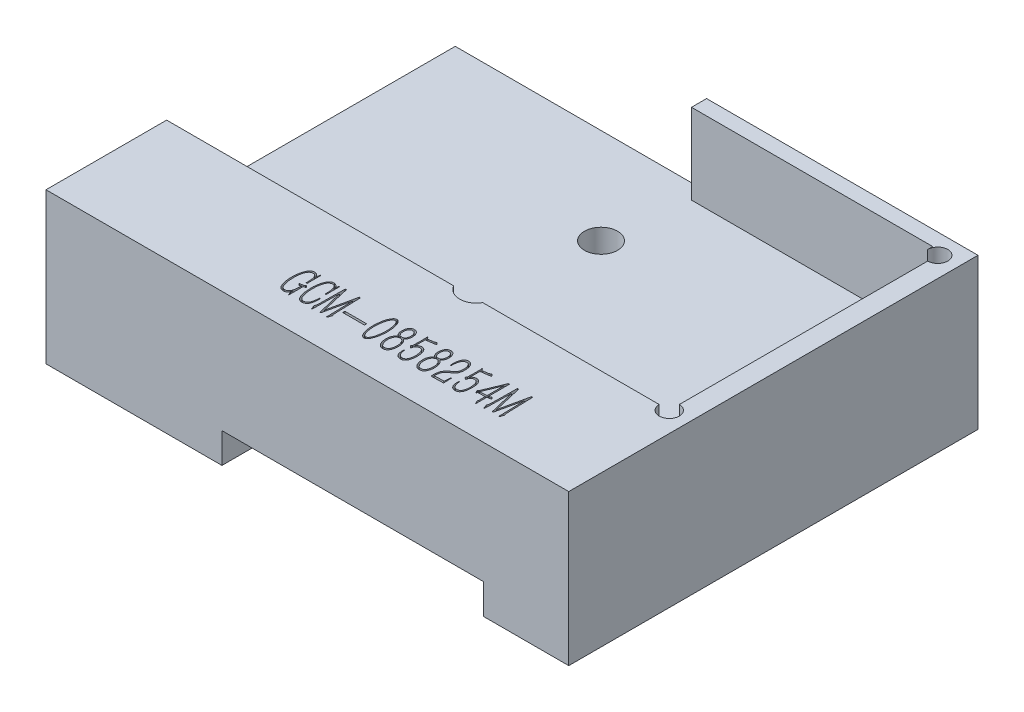
SolidWorks part; units mm, degrees
material "6061 合金"
ref_plane "前视基准面" through (0, 0, 0) normal (0, 0, 1) x (1, 0, 0)
ref_plane "上视基准面" through (0, 0, 0) normal (0, 1, 0) x (1, 0, 0)
ref_plane "右视基准面" through (0, 0, 0) normal (1, 0, 0) x (0, 0, -1)
sketch "草图1" plane through (0, 0, 0) normal (0, 1, 0) x (1, 0, 0)
  line L1 (-25, 13.355) -> (25, 13.355)
  line L2 (-25, 13.355) -> (-25, -13.355)
  line L3 (-25, -13.355) -> (25, -13.355)
  line L4 (25, 13.355) -> (25, -13.355)
  line L5 (-25, 13.355) -> (25, -13.355) construction
  line L6 (-25, -13.355) -> (25, 13.355) construction
  point P0 (0, 0)
  dimension "D1" = 50
  dimension "D2" = 26.71
extrude "凸台-拉伸1" add sketch "草图1" along normal blind 6
sketch "草图2" plane through (0, 6, 0) normal (0, 1, 0) x (1, 0, 0)
  line L1 (25, 13.355) -> (-25, 13.355) construction
  line L3 (25, 13.355) -> (-25, 13.355)
  line L12 (-25, -13.355) -> (25, -13.355) construction
  line L13 (-25, -13.355) -> (25, -13.355)
  line L19 (25, -13.355) -> (25, 13.355) construction
  line L20 (25, -13.355) -> (25, 13.355)
  line L21 (-25, -15.355) -> (27, -15.355)
  line L22 (27, -15.355) -> (27, 15.355)
  line L23 (27, 15.355) -> (-25, 15.355)
  line L24 (-25, -15.355) -> (-25, -13.355)
  line L25 (-25, 13.355) -> (-25, 15.355)
  dimension "D1" = 2
extrude "凸台-拉伸2" add sketch "草图2" along normal blind 8 and the other way through all
sketch "草图3" plane through (0, 6, 0) normal (0, 1, 0) x (1, 0, 0)
  line L0 (-1, 13.355) -> (-1, 5.855) construction
  line L1 (25, -13.355) -> (25, 13.355) construction
  line L3 (25, 13.355) -> (-25, 13.355) construction
  line L5 (-1, 5.855) -> (25, 5.855) construction
  circle A0 centre (-1, 5.855) radius 1.3881
  dimension "D1" = 7.5
  dimension "D2" = 26
hole_wizard "M4 螺纹孔1" [suppressed] positions "3D草图1" profile "草图4" tap size "M4" standard "GB"
sketch3d "3D草图1"
  point P0 (-1, 6, -5.855)
sketch "草图4" plane through (-1, 6, -5.855) normal (1, 0, 0) x (0, 0, 1)
  line L0 (0, 0) -> (0, 11.0914)
  line L1 (0, 11.0914) -> (1.65, 10.1)
  line L2 (1.65, 10.1) -> (1.65, 0)
  line L5 (1.65, 0) -> (0, 0)
  line L10 (0, 11.0914) -> (-1.65, 10.1) construction
  line L11 (0, -6.35) -> (0, 107.95) construction
  dimension "螺纹孔钻头直径" = 3.3
  dimension "螺纹孔钻头深度" = 10.1
  dimension "导头角度" = 118
cosmetic thread "孔螺蚊线1" [suppressed] parameters "D1"=2.4, "D2"=4
sketch "草图12" plane through (-25, 0, 0) normal (-1, 0, 0) x (0, 0, 1)
  line L1 (-13.355, 6) -> (-15.355, 6)
  line L2 (-13.355, 6) -> (-13.355, 14)
  line L3 (-13.355, 14) -> (-15.355, 14)
  line L4 (-15.355, 6) -> (-15.355, 14)
extrude "切除-拉伸5" cut sketch "草图12" against normal blind 25
sketch "草图13" plane through (0, 14, 0) normal (0, 1, 0) x (1, 0, 0)
  circle A0 centre (25, -13.355) radius 1
  circle A1 centre (25, 13.355) radius 1
extrude "切除-拉伸6" cut sketch "草图13" against normal up to surface (8 mm away) up to face at (0, 6, -5.1183)
sketch "草图15" plane through (0, 0, 15.355) normal (0, 0, 1) x (1, 0, 0)
  line L4 (27, 0) -> (27, 14)
  line L5 (27, 14) -> (-25, 14)
  line L6 (-25, 14) -> (-25, 0)
  line L7 (-25, 0) -> (27, 0)
  line L8 (27, 0) -> (27, 14)
  line L9 (27, 14) -> (-25, 14)
  line L10 (-25, 14) -> (-25, 0)
  line L11 (-25, 0) -> (27, 0)
  dimension "D1" = 0
extrude "凸台-拉伸3" add sketch "草图15" along normal blind 10
sketch "草图5" plane through (0, 0, 0) normal (0, -1, 0) x (1, 0, 0)
  line L0 (-7.4968, 0.0619) -> (-7.4968, 25.0555) construction
  line L1 (-7.4968, 25.0555) -> (17.5032, 25.0555)
  line L2 (-7.4968, 25.0555) -> (-7.4968, 0.0555)
  line L3 (-7.4968, 0.0555) -> (17.5032, 0.0555)
  line L4 (17.5032, 25.0555) -> (17.5032, 0.0555)
  line L5 (-7.4968, 25.0555) -> (17.5032, 0.0555) construction
  line L6 (-7.4968, 0.0555) -> (17.5032, 25.0555) construction
  line L7 (-7.4968, 25.0555) -> (17.4968, 25.0555) construction
  circle A0 centre (5.0032, 12.5555) radius 1.1939
  dimension "D1" = 25
  dimension "D2" = 25
extrude "切除-拉伸1" cut sketch "草图5" against normal blind 2
sketch "草图6" plane through (0, 2, 0) normal (0, -1, 0) x (1, 0, 0)
  line L0 (5.0032, 25.0555) -> (5.0032, 0.0555) construction
  line L3 (5.0032, 12.5555) -> (-7.4968, 12.5555) construction
  line L6 (-7.4968, 25.0555) -> (-7.4968, 0.0555) construction
  line L8 (17.5032, 25.0555) -> (-7.4968, 25.0555) construction
  dimension "D1" = 25
  dimension "D2" = 12.5
hole_wizard "M4 螺纹孔2" positions "3D草图2" profile "草图7" tap size "M4" standard "GB" end condition through all
sketch3d "3D草图2"
  point P0 (5.0032, 2, 12.5555)
cosmetic thread "孔螺蚊线2" parameters "D2"=4
sketch "草图7" plane through (5.0032, 2, 12.5555) normal (1, 0, 0) x (0, 0, -1)
  line L0 (0, 0) -> (0, 12)
  line L1 (0, 12) -> (1.65, 12)
  line L2 (1.65, 12) -> (1.65, 0)
  line L5 (1.65, 0) -> (0, 0)
  line L11 (0, -6.35) -> (0, 107.95) construction
  dimension "通孔螺纹孔钻头直径" = 3.3
  dimension "通孔螺纹孔钻头深度" = 12
sketch "草图16" plane through (0, 0, 25.0555) normal (0, 0, -1) x (-1, 0, 0)
  line L4 (-17.5032, 0) -> (7.4968, 0)
  line L5 (7.4968, 0) -> (7.4968, 2)
  line L6 (7.4968, 2) -> (-17.5032, 2)
  line L7 (-17.5032, 2) -> (-17.5032, 0)
  line L8 (-17.5032, 0) -> (7.4968, 0)
  line L9 (7.4968, 0) -> (7.4968, 2)
  line L10 (7.4968, 2) -> (-17.5032, 2)
  line L11 (-17.5032, 2) -> (-17.5032, 0)
  dimension "D1" = 0
extrude "切除-拉伸7" cut sketch "草图16" against normal through all
sketch "草图17" plane through (17.5032, 0, 0) normal (-1, 0, 0) x (0, 0, 1)
  line L4 (0.0555, 0) -> (25.355, 0)
  line L5 (25.355, 0) -> (25.355, 2)
  line L6 (25.355, 2) -> (0.0555, 2)
  line L7 (0.0555, 2) -> (0.0555, 0)
  line L8 (0.0555, 0) -> (25.355, 0)
  line L9 (25.355, 0) -> (25.355, 2)
  line L10 (25.355, 2) -> (0.0555, 2)
  line L11 (0.0555, 2) -> (0.0555, 0)
  dimension "D1" = 0
extrude "切除-拉伸8" cut sketch "草图17" against normal blind 1
sketch "草图18" plane through (0, 0, 0) normal (0, -1, 0) x (-1, 0, 0)
  circle A0 centre (7.4968, -0.0555) radius 1
extrude "切除-拉伸9" cut sketch "草图18" against normal up to surface (2 mm away) up to face at (5.0032, 2, 10.9055)
fillet "圆角1" radius 1 1 edges at (18.5032, 1, 0.0555)
sketch "草图19" plane through (0, 0, -13.355) normal (0, 0, 1) x (1, 0, 0)
  line L4 (24, 14) -> (0, 14)
  line L5 (0, 14) -> (0, 6)
  line L6 (0, 6) -> (24, 6)
  line L7 (24, 6) -> (24, 14)
  line L8 (24, 14) -> (0, 14)
  line L9 (0, 14) -> (0, 6)
  line L10 (0, 6) -> (24, 6)
  line L12 (24, 6) -> (24, 14)
  dimension "D1" = 0
extrude "切除-拉伸10" cut sketch "草图19" against normal blind 0.5
sketch "草图20" plane through (0, 14, 0) normal (0, 1, 0) x (1, 0, 0)
  text T0 "GCM-0858254M "
extrude "切除-拉伸11" cut sketch "草图20" against normal blind 0.5
sketch "草图21" plane through (0, 0, 0) normal (0, -1, 0) x (1, 0, 0)
  line L8 (17.5032, 0.0555) -> (-6.4968, 0.0555)
  line L9 (-7.4968, 1.0555) -> (-7.4968, 25.355)
  line L10 (-7.4968, 25.355) -> (-25, 25.355)
  line L11 (-25, 25.355) -> (-25, -15.355)
  line L12 (-25, -15.355) -> (27, -15.355)
  line L13 (27, -15.355) -> (27, 25.355)
  line L14 (27, 25.355) -> (18.5032, 25.355)
  line L15 (18.5032, 25.355) -> (18.5032, 1.0555)
  line L16 (17.5032, 0.0555) -> (-6.4968, 0.0555)
  line L17 (-7.4968, 1.0555) -> (-7.4968, 25.355)
  line L18 (-7.4968, 25.355) -> (-25, 25.355)
  line L19 (-25, 25.355) -> (-25, -15.355)
  line L20 (-25, -15.355) -> (27, -15.355)
  line L21 (27, -15.355) -> (27, 25.355)
  line L22 (27, 25.355) -> (18.5032, 25.355)
  line L23 (18.5032, 25.355) -> (18.5032, 1.0555)
  arc A2 (-7.4968, 1.0555) -> (-6.4968, 0.0555) centre (-7.4968, 0.0555) ccw
  arc A3 (17.5032, 0.0555) -> (18.5032, 1.0555) centre (17.5032, 1.0555) ccw
  arc A4 (-7.4968, 1.0555) -> (-6.4968, 0.0555) centre (-7.4968, 0.0555) ccw
  arc A5 (17.5032, 0.0555) -> (18.5032, 1.0555) centre (17.5032, 1.0555) ccw
  dimension "D1" = 0
extrude "凸台-拉伸4" add sketch "草图21" along normal blind 1
hole_wizard "M4 螺纹孔3" positions "3D草图3" profile "草图22" tap size "M4" standard "GB" end condition through all
sketch3d "3D草图3"
  point P0 (-1, 6, -5.855)
sketch "草图22" plane through (-1, 6, -5.855) normal (1, 0, 0) x (0, 0, 1)
  line L0 (0, 0) -> (0, 7)
  line L1 (0, 7) -> (1.65, 7)
  line L2 (1.65, 7) -> (1.65, 0)
  line L5 (1.65, 0) -> (0, 0)
  line L11 (0, -6.35) -> (0, 107.95) construction
  dimension "通孔螺纹孔钻头直径" = 3.3
  dimension "通孔螺纹孔钻头深度" = 7
cosmetic thread "孔螺蚊线3" parameters "D2"=4
